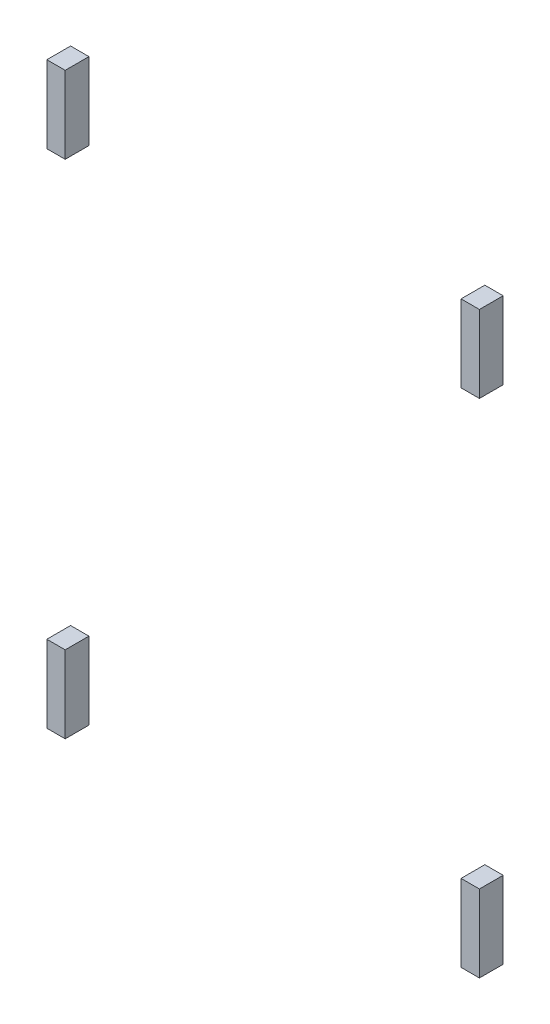
SolidWorks part; units mm, degrees
ref_plane "Front Plane" through (0, 0, 0) normal (0, 0, 1) x (1, 0, 0)
ref_plane "Top Plane" through (0, 0, 0) normal (0, 1, 0) x (1, 0, 0)
ref_plane "Right Plane" through (0, 0, 0) normal (1, 0, 0) x (0, 0, -1)
ref_plane "Plane2" through (280.55, 0, 0) normal (1, 0, 0) x (0, 0, -1)
sketch "Sketch5" plane through (280.55, 0, 0) normal (1, 0, 0) x (0, 0, -1)
  line L0 (-1970.8, -500) -> (-1970.8, -400)
  line L1 (-1970.8, -400) -> (-2001.6, -400)
  line L2 (-2001.6, -400) -> (-2001.6, -500)
  line L3 (-2001.6, -500) -> (-1970.8, -500)
extrude "Boss-Extrude2" add sketch "Sketch5" against normal blind 23.8 separate body
sketch "Sketch10" plane through (280.55, 0, 0) normal (1, 0, 0) x (0, 0, -1)
  line L0 (-1970.8, 151) -> (-1970.8, 251)
  line L1 (-1970.8, 251) -> (-2001.6, 251)
  line L2 (-2001.6, 251) -> (-2001.6, 151)
  line L3 (-2001.6, 151) -> (-1970.8, 151)
  line L4 (-1970.8, -400) -> (-2001.6, -400) construction
  dimension "D1" = 551
extrude "Boss-Extrude3" add sketch "Sketch10" against normal blind 23.8 separate body
ref_plane "Plane3" through (-280.55, 0, 0) normal (-1, 0, 0) x (0, 0, 1)
sketch "Sketch15" plane through (-280.55, 0, 0) normal (-1, 0, 0) x (0, 0, 1)
  line L0 (1970.8, -500) -> (2001.6, -500)
  line L1 (2001.6, -500) -> (2001.6, -400)
  line L2 (2001.6, -400) -> (1970.8, -400)
  line L3 (1970.8, -400) -> (1970.8, -500)
extrude "Boss-Extrude4" add sketch "Sketch15" against normal blind 23.8 separate body
sketch "Sketch21" plane through (-280.55, 0, 0) normal (-1, 0, 0) x (0, 0, 1)
  line L0 (1970.8, 151) -> (2001.6, 151)
  line L1 (2001.6, 151) -> (2001.6, 251)
  line L2 (2001.6, 251) -> (1970.8, 251)
  line L3 (1970.8, 251) -> (1970.8, 151)
  line L4 (2001.6, -400) -> (1970.8, -400) construction
  dimension "D1" = 551
extrude "Boss-Extrude5" add sketch "Sketch21" against normal blind 23.8 separate body
